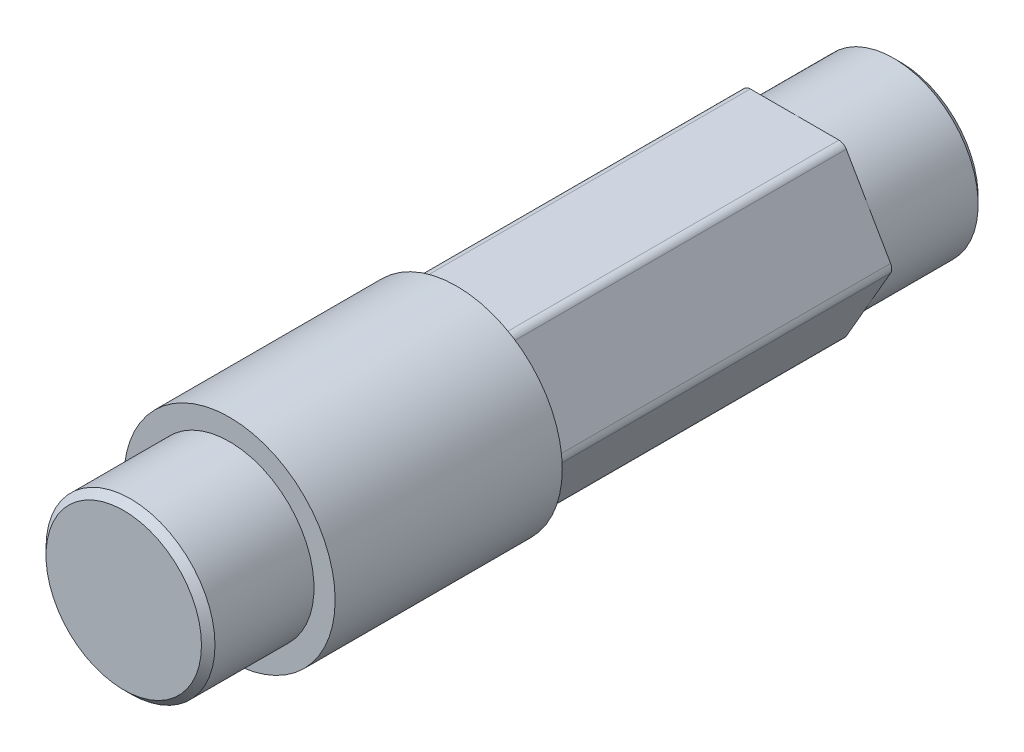
SolidWorks part; units mm, degrees
material "6061-T6 (SS)"
ref_plane "Front Plane" through (0, 0, 0) normal (0, 0, 1) x (1, 0, 0)
ref_plane "Top Plane" through (0, 0, 0) normal (0, 1, 0) x (1, 0, 0)
ref_plane "Right Plane" through (0, 0, 0) normal (1, 0, 0) x (0, 0, -1)
sketch "Sketch1" plane through (0, 0, 0) normal (1, 0, 0) x (0, 0, -1)
  line L0 (0, 0) -> (-9978.08, 0) construction
  line L1 (0, 14.3962) -> (0, 0) construction
  line L2 (-25.019, 0) -> (-25.019, 6.35)
  line L3 (-25.019, 6.35) -> (-17.0688, 6.35)
  line L4 (-17.0688, 6.35) -> (-17.0688, 7.9375)
  line L5 (-17.0688, 7.9375) -> (0, 7.9375)
  line L6 (0, 7.9375) -> (0, 7.62)
  line L7 (0, 7.62) -> (25.4, 7.62)
  line L8 (25.4, 7.62) -> (25.4, 6.35)
  line L9 (25.4, 6.35) -> (33.3502, 6.35)
  line L10 (33.3502, 6.35) -> (33.3502, 0)
  line L11 (-25.019, 0) -> (33.3502, 0)
  dimension "D1" = 7.9502
  dimension "D2" = 15.875
  dimension "D3" = 15.24
  dimension "D4" = 12.7
  dimension "D5" = 25.4
  dimension "D6" = 17.0688
revolve "Revolve1" add sketch "Sketch1" angle 360 about L0
sketch "Sketch2" plane through (0, 0, -25.4) normal (0, 0, -1) x (-1, 0, 0)
  line L1 (3.697, 6.4033) -> (-3.697, 6.4033)
  line L2 (-3.697, 6.4033) -> (-7.3939, 0)
  line L3 (-7.3939, 0) -> (-3.697, -6.4033)
  line L4 (-3.697, -6.4033) -> (3.697, -6.4033)
  line L5 (3.697, -6.4033) -> (7.3939, 0)
  line L6 (7.3939, 0) -> (3.697, 6.4033)
  circle A0 centre (0, 0) radius 6.4033 construction
  dimension "D1" = 12.8067
extrude "Cut-Extrude1" cut sketch "Sketch2" against normal up to surface (25.4 mm away) flip side to cut up to face at (-7.9375, 0, 0)
chamfer "Chamfer1" distance 0.508 angle 45 2 edges at (-6.35, 0, -33.3502) (-6.35, 0, 25.019)
sketch "Sketch3" plane through (0, 0, -33.3502) normal (0, 0, -1) x (-1, 0, 0)
  circle A0 centre (0, 0) radius 3.175
  dimension "D1" = 6.35
extrude "Cut-Extrude2" cut sketch "Sketch3" against normal blind 6.858
fillet "Fillet1" radius 0.635 6 edges at (3.697, 6.4033, -12.7) (7.3939, 0, -12.7) (3.697, -6.4033, -12.7) (-3.697, -6.4033, -12.7) (-7.3939, 0, -12.7) (-3.697, 6.4033, -12.7)
